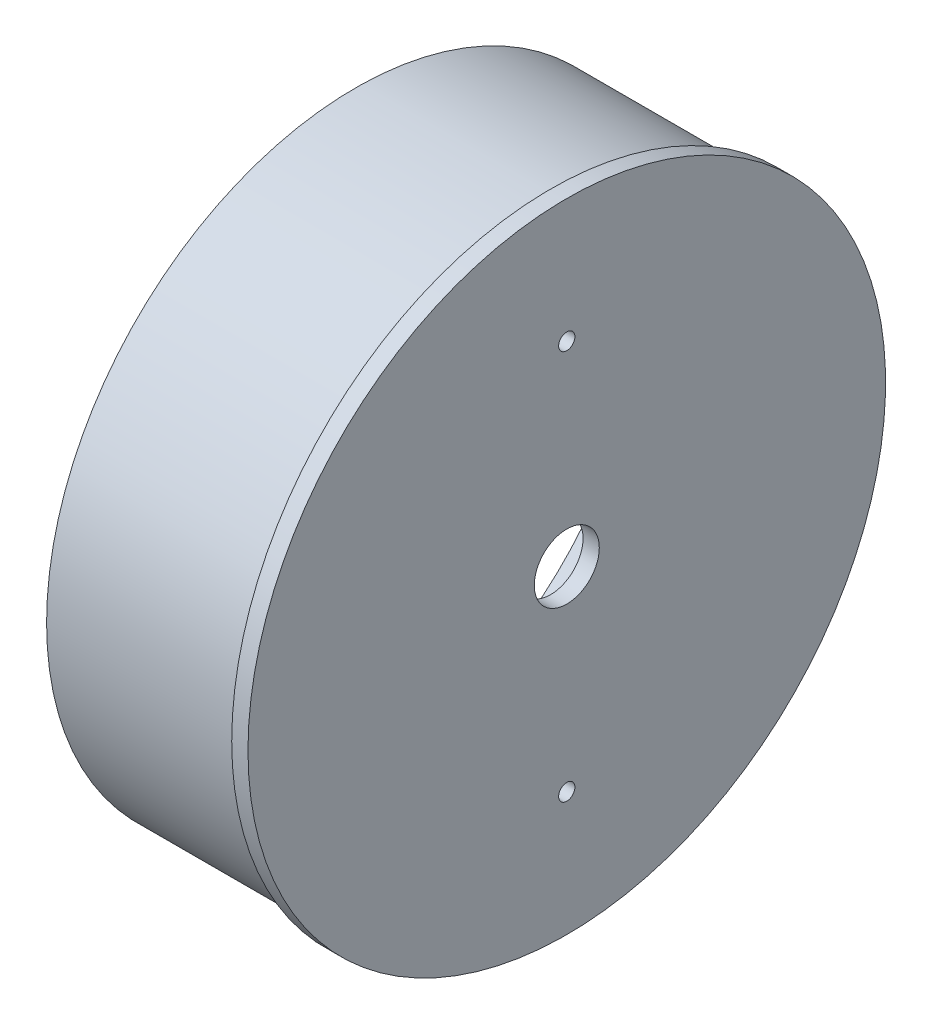
SolidWorks part; units mm, degrees
ref_plane "Front Plane" through (0, 0, 0) normal (0, 0, 1) x (1, 0, 0)
ref_plane "Top Plane" through (0, 0, 0) normal (0, 1, 0) x (1, 0, 0)
ref_plane "Right Plane" through (0, 0, 0) normal (1, 0, 0) x (0, 0, -1)
sketch "Sketch1" plane through (0, 0, 0) normal (0, 0, 1) x (1, 0, 0)
  line L0 (1050.0264, 25.7416) -> (-92.9736, 25.7416) construction
  line L1 (7.1264, 25.2416) -> (9.6264, 25.2416)
  line L2 (7.1264, 25.2416) -> (7.1264, -23.7884)
  line L3 (7.1264, -23.7884) -> (9.6264, -23.7884)
  line L4 (9.6264, 25.2416) -> (9.6264, -23.7884)
  line L5 (7.1264, 23.7116) -> (-22.8736, 23.7116)
  line L6 (7.1264, 23.7116) -> (7.1264, 21.2116)
  line L7 (7.1264, 21.2116) -> (-22.8736, 21.2116)
  line L8 (-22.8736, 23.7116) -> (-22.8736, 21.2116)
  line L9 (7.1264, 24.2116) -> (-192.8736, 24.2116) construction
  line L10 (1807.1859, -23.7884) -> (1562.8669, -23.7884) construction
  dimension "D2" = 0.5
  dimension "D3" = 30
  dimension "D4" = 2.5
  dimension "D5" = 2.5
  dimension "D6" = 0.5
  dimension "D7" = 0
revolve "Revolve1" add sketch "Sketch1" angle 360 about L3
sketch "Sketch2" plane through (9.6264, 0, 0) normal (1, 0, 0) x (0, 0, -1)
  line L0 (0, 25.2416) -> (0, -72.8184)
  line L1 (0, -23.7884) -> (22.1708, -23.7884) construction
  circle A0 centre (0, -23.7884) radius 49.03 construction
  circle A1 centre (0, -23.7884) radius 5
  circle A2 centre (0, -53.7884) radius 1.25
  circle A3 centre (0, 6.2116) radius 1.25
  dimension "D1" = 2.5
  dimension "D2" = 30
extrude "Cut-Extrude1" cut sketch "Sketch2" against normal blind 10 contours L0 A1 | L0 L1 A1 | L1 L0 A1 | L0 A2 | L0 A2 | A3 L0 | A3 L0
